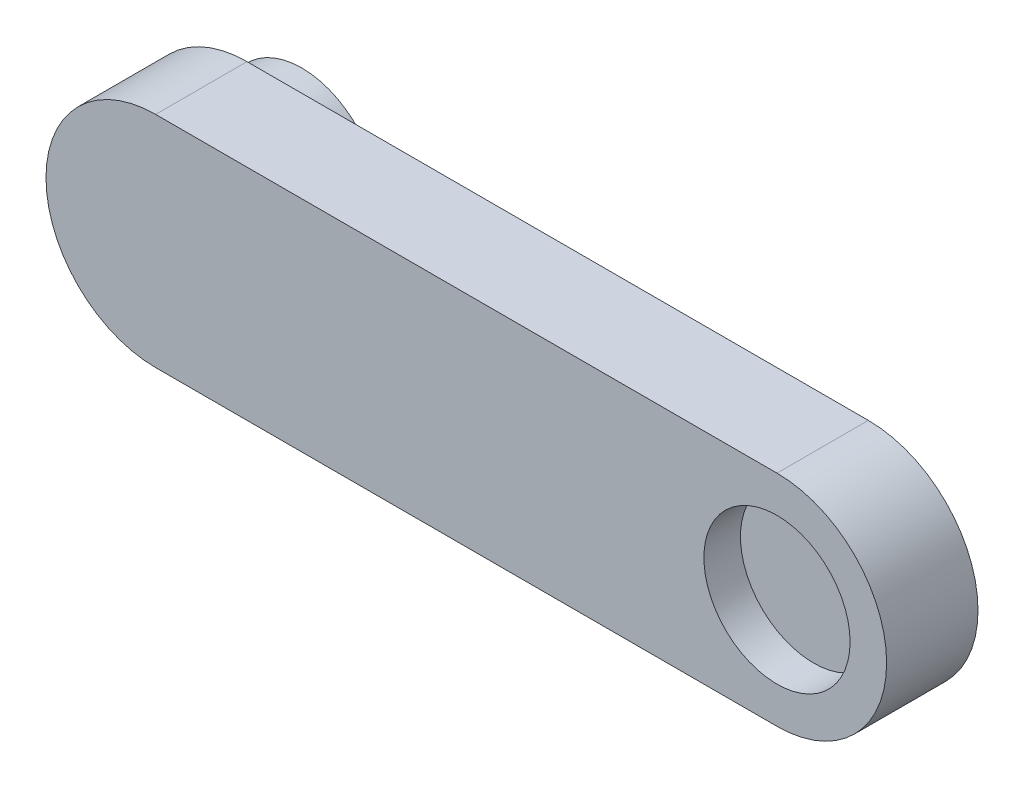
SolidWorks part; units mm, degrees
ref_plane "Alzado" through (0, 0, 0) normal (0, 0, 1) x (1, 0, 0)
ref_plane "Planta" through (0, 0, 0) normal (0, 1, 0) x (1, 0, 0)
ref_plane "Vista lateral" through (0, 0, 0) normal (1, 0, 0) x (0, 0, -1)
sketch "Croquis2" plane through (0, 0, 0) normal (0, 0, 1) x (1, 0, 0)
  line L0 (-85, 0) -> (85, 0) construction
  line L1 (-85, 30) -> (85, 30)
  line L2 (-85, -30) -> (85, -30)
  arc A0 (-85, 30) -> (-85, -30) centre (-85, 0) ccw
  arc A1 (85, -30) -> (85, 30) centre (85, 0) ccw
  point P2 (0, 0)
  dimension "D2" = 170
  dimension "D1" = 60
extrude "Saliente-Extruir1" add sketch "Croquis2" along normal blind 25
sketch "Croquis3" plane through (0, 0, 0) normal (0, 0, -1) x (-1, 0, 0)
  circle A0 centre (85, 0) radius 21
  point P5 (108.7977, -1.681)
  dimension "D1" = 42
  dimension "D2" = 30
  dimension "D3" = 0
extrude "Saliente-Extruir2" add sketch "Croquis3" along normal blind 15
sketch "Croquis4" plane through (0, 0, 25) normal (0, 0, 1) x (1, 0, 0)
  circle A0 centre (85, 0) radius 20
  point P2 (0, 0)
  point P4 (0, 0)
  dimension "D1" = 40
  dimension "D2" = 30
  dimension "D3" = 0
extrude "Cortar-Extruir1" cut sketch "Croquis4" against normal blind 10
